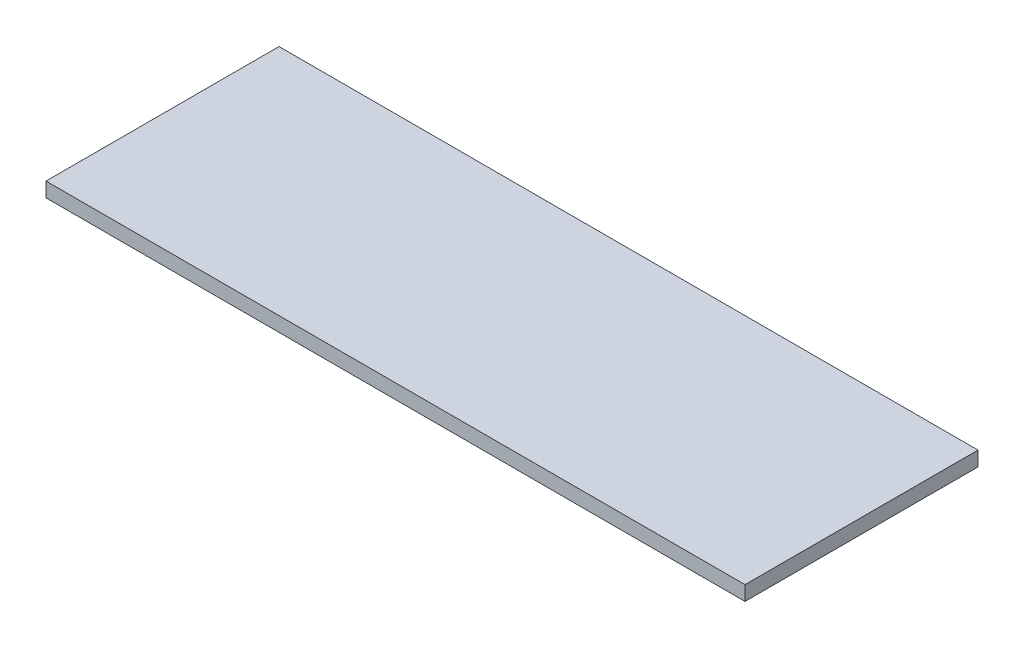
SolidWorks part; units mm, degrees
ref_plane "Front Plane" through (0, 0, 0) normal (0, 0, 1) x (1, 0, 0)
ref_plane "Top Plane" through (0, 0, 0) normal (0, 1, 0) x (1, 0, 0)
ref_plane "Right Plane" through (0, 0, 0) normal (1, 0, 0) x (0, 0, -1)
sketch "Sketch1" plane through (0, 0, 0) normal (0, 1, 0) x (1, 0, 0)
  line L1 (0, 25.4) -> (76.2, 25.4)
  line L2 (0, 25.4) -> (0, 0)
  line L3 (0, 0) -> (76.2, 0)
  line L4 (76.2, 25.4) -> (76.2, 0)
  dimension "D1" = 25.4
  dimension "D2" = 76.2
extrude "Boss-Extrude1" add sketch "Sketch1" along normal blind 1.5875
